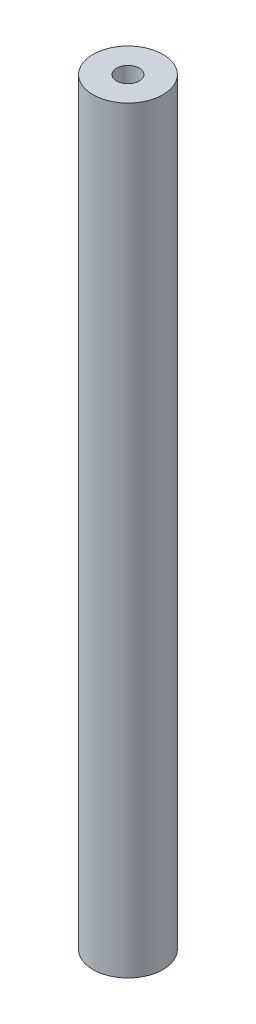
SolidWorks part; units mm, degrees
ref_plane "Front Plane" through (0, 0, 0) normal (0, 0, 1) x (1, 0, 0)
ref_plane "Top Plane" through (0, 0, 0) normal (0, 1, 0) x (1, 0, 0)
ref_plane "Right Plane" through (0, 0, 0) normal (1, 0, 0) x (0, 0, -1)
sketch "Sketch1" plane through (0, 0, 0) normal (0, 1, 0) x (1, 0, 0)
  circle A0 centre (-6.5536, 4.9152) radius 4.5
  dimension "D1" = 9
extrude "Boss-Extrude1" add sketch "Sketch1" along normal blind 97.5
sketch "Sketch2" plane through (0, 97.5, 0) normal (0, 1, 0) x (1, 0, 0)
  circle A0 centre (-6.5536, 4.9152) radius 1.45
  dimension "D1" = 2.9
extrude "Cut-Extrude1" cut sketch "Sketch2" against normal blind 97.5 contours A0
